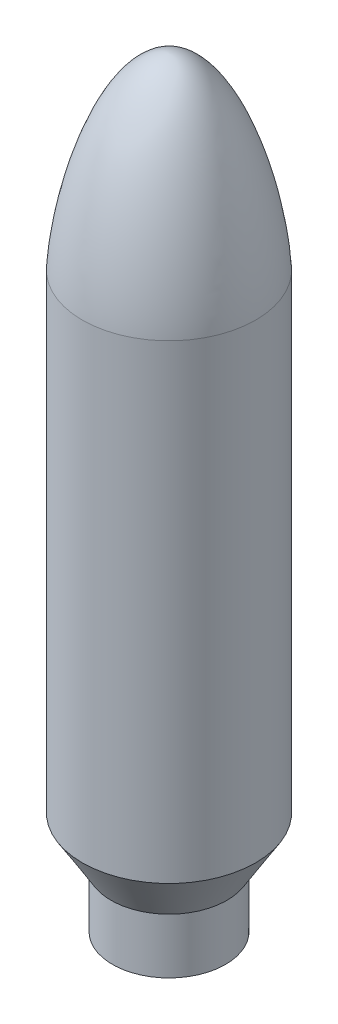
SolidWorks part; units mm, degrees
ref_plane "Front Plane" through (0, 0, 0) normal (0, 0, 1) x (1, 0, 0)
ref_plane "Top Plane" through (0, 0, 0) normal (0, 1, 0) x (1, 0, 0)
ref_plane "Right Plane" through (0, 0, 0) normal (1, 0, 0) x (0, 0, -1)
sketch "Sketch1" plane through (0, 0, 0) normal (0, 0, 1) x (1, 0, 0)
  line L0 (-12.065, 0) -> (-12.065, 12)
  line L1 (-12.065, 12) -> (-12.369, 12)
  line L2 (-12.369, 12) -> (-18.5, 22)
  line L3 (-18.5, 22) -> (-18.5, 122.2821)
  line L4 (-18.5, 122.2821) -> (-17.5, 122.2821)
  line L5 (-17.5, 122.2821) -> (-17.5, 22.2821)
  line L6 (-17.5, 22.2821) -> (-11.8091, 13)
  line L7 (-11.8091, 13) -> (-11.065, 13)
  line L8 (-11.065, 13) -> (-11.065, 0)
  line L9 (-11.065, 0) -> (-12.065, 0)
  line L10 (0, 0) -> (0, 43.0418) construction
  dimension "D1" = 1
  dimension "D2" = 12.065
  dimension "D3" = 12.369
  dimension "D4" = 1
  dimension "D5" = 1
  dimension "D6" = 1
  dimension "D7" = 10
  dimension "D8" = 17.5
  dimension "D9" = 12
  dimension "D10" = 0
  dimension "D11" = 100
revolve "Revolve1" add sketch "Sketch1" angle 360 about L10
sketch "Sketch2" plane through (0, 0, 0) normal (0, 0, 1) x (1, 0, 0)
  line L0 (0, 122.2821) -> (0, 181.6557) construction
  line L1 (17.5, 122.2821) -> (-17.5, 122.2821) construction
  line L2 (0, 118.2821) -> (-16.3, 118.2821)
  line L4 (-17.3, 119.2821) -> (-17.3, 122.2821)
  line L5 (-17.3, 122.2821) -> (-18.5, 122.2821)
  line L6 (0, 118.2821) -> (0, 162.2821)
  line L8 (-18.5, 122.2821) -> (-17.7086, 136.9926) construction
  line L9 (-17.7086, 136.9926) -> (-10.5218, 161.697) construction
  line L10 (-10.5218, 161.697) -> (0, 162.2821) construction
  line L11 (-16.3, 118.2821) -> (-17.3, 119.2821)
  spline S0 degree 3 poles (-18.5, 122.2821) (-17.7086, 136.9926) (-10.5218, 161.697) (0, 162.2821) knots 0 0 0 0 1 1 1 1
  point P6 (-17.3, 118.2821)
  dimension "D1" = 4
  dimension "D2" = 40
  dimension "D3" = 1.2
revolve "Revolve3" add sketch "Sketch2" angle 360 about L0
other "Save Bodies1"
other "Save Bodies2"
